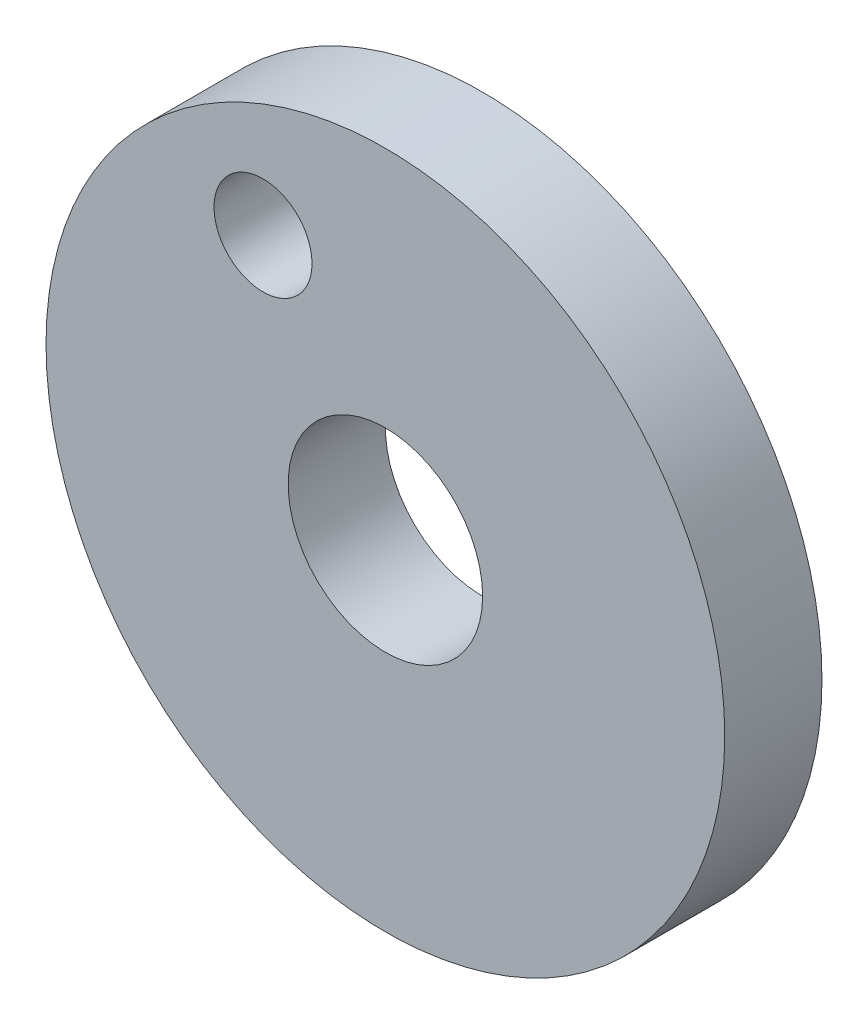
SolidWorks part; units mm, degrees
ref_plane "正面" through (0, 0, 0) normal (0, 0, 1) x (1, 0, 0)
ref_plane "平面" through (0, 0, 0) normal (0, 1, 0) x (1, 0, 0)
ref_plane "右側面" through (0, 0, 0) normal (1, 0, 0) x (0, 0, -1)
sketch "ｽｹｯﾁ1" plane through (0, 0, 0) normal (0, 0, 1) x (1, 0, 0)
  circle A0 centre (0, 0) radius 34.9
  circle A1 centre (0, 0) radius 10
  circle A2 centre (-12.5847, 20.8495) radius 5.04
extrude "ﾎﾞｽ - 押し出し1" add sketch "ｽｹｯﾁ1" along normal blind 10
